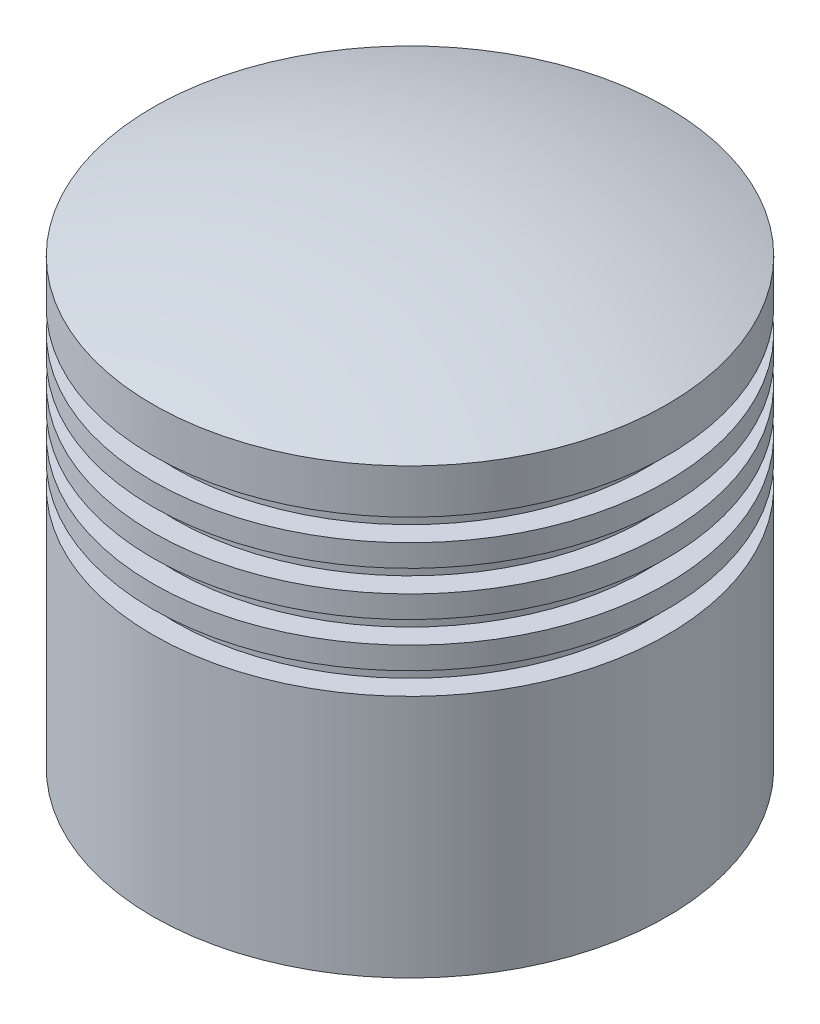
SolidWorks part; units mm, degrees
ref_plane "Front Plane" through (0, 0, 0) normal (0, 0, 1) x (1, 0, 0)
ref_plane "Top Plane" through (0, 0, 0) normal (0, 1, 0) x (1, 0, 0)
ref_plane "Right Plane" through (0, 0, 0) normal (1, 0, 0) x (0, 0, -1)
sketch "Sketch1" plane through (0, 0, 0) normal (0, 0, 1) x (1, 0, 0)
  line L0 (0, 0) -> (0, 94326.764) construction
  line L1 (0, 0) -> (94326.764, 0) construction
  line L2 (58, 0) -> (58, 55)
  line L3 (58, 55) -> (53, 55)
  line L4 (53, 55) -> (53, 60)
  line L5 (53, 60) -> (58, 60)
  line L6 (58, 60) -> (58, 65)
  line L7 (58, 65) -> (53, 65)
  line L8 (53, 65) -> (53, 70)
  line L9 (53, 70) -> (58, 70)
  line L10 (58, 70) -> (58, 75)
  line L11 (58, 75) -> (53, 75)
  line L12 (53, 75) -> (53, 80)
  line L13 (53, 80) -> (58, 80)
  line L14 (58, 80) -> (58, 85)
  line L15 (58, 85) -> (53, 85)
  line L16 (53, 85) -> (53, 90)
  line L17 (53, 90) -> (58, 90)
  line L18 (58, 90) -> (58, 100)
  line L22 (43, 97.4261) -> (43, 30)
  line L23 (43, 30) -> (50, 30)
  line L24 (50, 30) -> (50, 0)
  line L25 (50, 0) -> (58, 0)
  line L26 (0, 110.2001) -> (0, 103.2001)
  arc A0 (43, 97.4261) -> (0, 103.2001) centre (0, -59.7999) ccw
  arc A1 (58, 100) -> (0, 110.2001) centre (0, -59.7999) ccw
  point P30 (0, -59.7999)
  point P31 (0, -59.819)
  point P32 (0, -59.7999)
  dimension "D22" = 170
  dimension "D23" = 163
  dimension "D1" = 43
  dimension "D2" = 7
  dimension "D3" = 8
  dimension "D4" = 5
  dimension "D5" = 5
  dimension "D6" = 5
  dimension "D7" = 5
  dimension "D8" = 5
  dimension "D9" = 5
  dimension "D10" = 5
  dimension "D11" = 5
  dimension "D12" = 5
  dimension "D13" = 5
  dimension "D14" = 5
  dimension "D15" = 5
  dimension "D16" = 5
  dimension "D17" = 5
  dimension "D18" = 5
  dimension "D19" = 30
  dimension "D20" = 90
  dimension "D21" = 100
revolve "Revolve1" add sketch "Sketch1" angle 360 about L0
